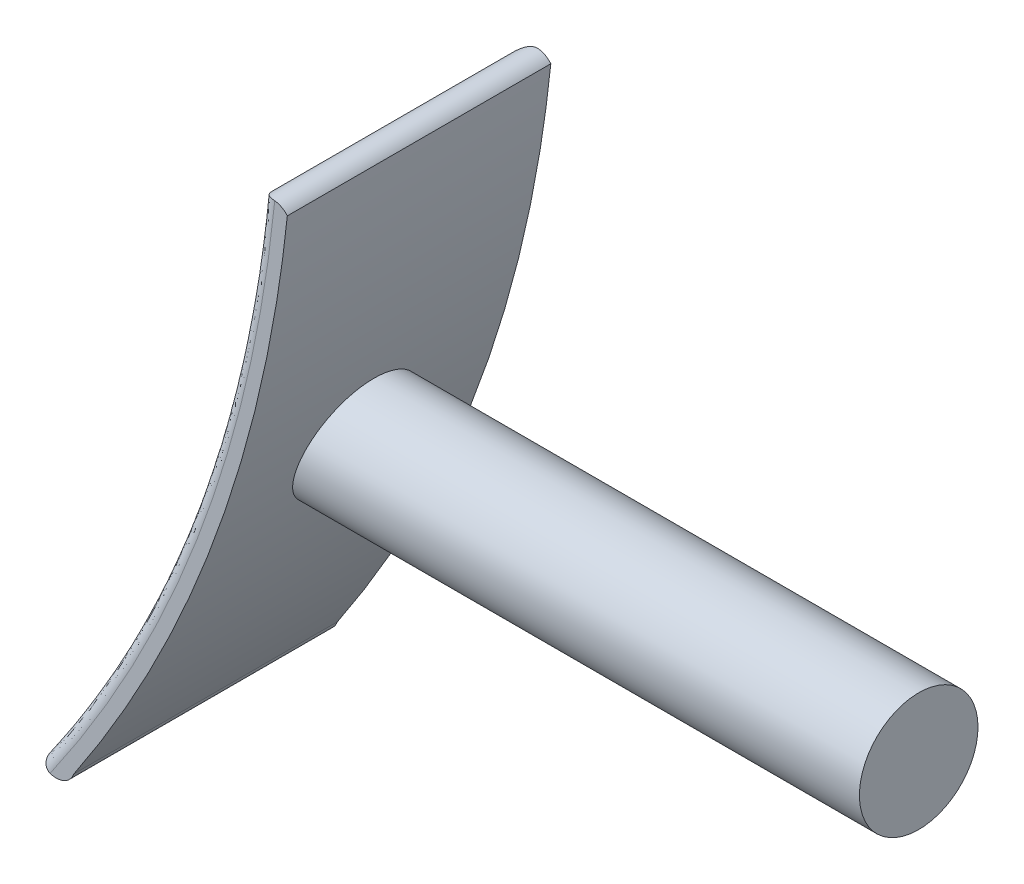
SolidWorks part; units mm, degrees
ref_plane "Front Plane" through (0, 0, 0) normal (0, 0, 1) x (1, 0, 0)
ref_plane "Top Plane" through (0, 0, 0) normal (0, 1, 0) x (1, 0, 0)
ref_plane "Right Plane" through (0, 0, 0) normal (1, 0, 0) x (0, 0, -1)
sketch "Sketch1" plane through (0, 0, 0) normal (0, 0, 1) x (1, 0, 0)
  arc A0 (-21.3156, -20.8244) -> (-18.0564, -20.5614) centre (-19.7464, -19.9445) ccw
  arc A1 (0, 36.5886) -> (2.5264, 36.3256) centre (1.1317, 35.1939) cw
  arc A2 (-21.3156, -20.8244) -> (-14.1016, -18.6032) centre (-17.8278, -19.3266) ccw construction
  arc A3 (-18.0564, -20.5614) -> (-16.5951, -19.0873) centre (-17.8278, -19.3266) ccw construction
  spline S0 degree 2 poles (0, 36.5886) (-3.2825, 5.0526) (-21.3156, -20.8244) knots 0 0 0 1 1 1
  spline S1 degree 1 poles (2.5264, 36.3256) (-18.0564, -20.5614) knots 0 0 1 1 construction
  spline S2 degree 2 poles (2.5264, 36.3256) (-0.7157, 5.1867) (-18.0564, -20.5614) knots 0 0 0 0.967614 0.967614 0.967614
  dimension "D2" = 57.15
  dimension "D3" = 57.15
  dimension "D1" = 2.54
extrude "Boss-Extrude1" add sketch "Sketch1" along normal blind 25.4
ref_plane "Plane1" through (2.54, 0, 0) normal (1, 0, 0) x (0, 0, -1)
sketch "Sketch2" plane through (2.54, 0, 0) normal (1, 0, 0) x (0, 0, -1)
  line L0 (-25.4, -20.5614) -> (0, -20.5614) construction
  line L1 (-25.4, 36.3256) -> (0, 36.3256) construction
  circle A0 centre (-12.8123, 8.6486) radius 5.715
  dimension "D1" = 11.43
  dimension "D2" = 29.21
  dimension "D3" = 27.677
extrude "Boss-Extrude2" add sketch "Sketch2" along normal blind 48.26 and the other way up to surface other way up to face at (-12.9107, -6.3397, 12.7)
fillet "Fillet1" radius 1.27 2 edges
